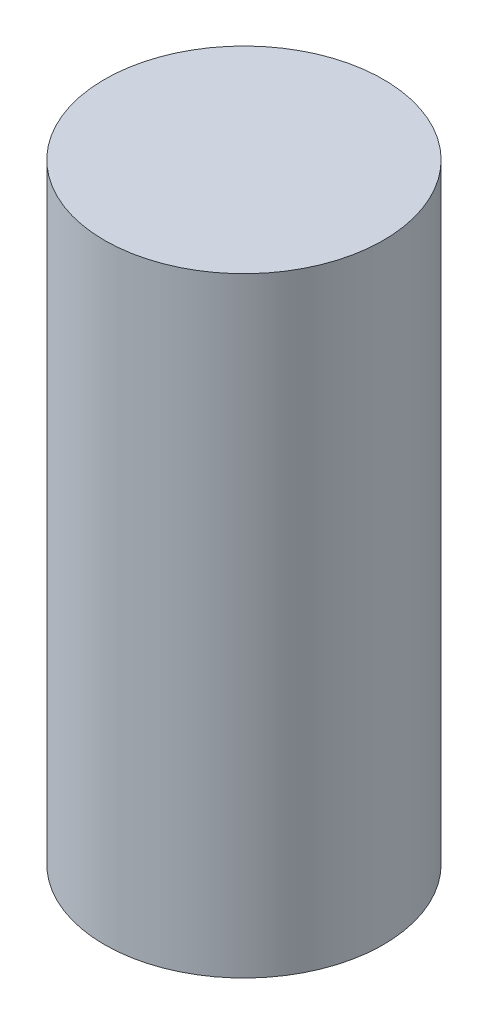
SolidWorks part; units mm, degrees
ref_plane "Front Plane" through (0, 0, 0) normal (0, 0, 1) x (1, 0, 0)
ref_plane "Top Plane" through (0, 0, 0) normal (0, 1, 0) x (1, 0, 0)
ref_plane "Right Plane" through (0, 0, 0) normal (1, 0, 0) x (0, 0, -1)
sketch "Sketch1" plane through (0, 0, 0) normal (0, 1, 0) x (1, 0, 0)
  circle A0 centre (0, 0) radius 228.6
  dimension "D1" = 457.2
extrude "Boss-Extrude1" add sketch "Sketch1" along normal blind 1000
